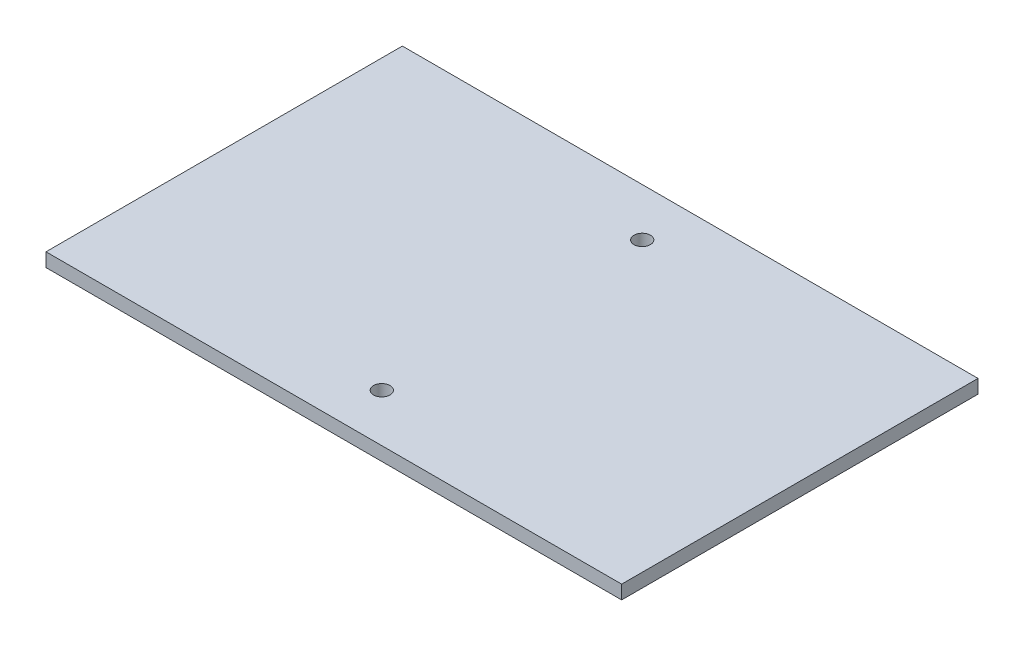
SolidWorks part; units mm, degrees
ref_plane "Front Plane" through (0, 0, 0) normal (0, 0, 1) x (1, 0, 0)
ref_plane "Top Plane" through (0, 0, 0) normal (0, 1, 0) x (1, 0, 0)
ref_plane "Right Plane" through (0, 0, 0) normal (1, 0, 0) x (0, 0, -1)
sketch "Sketch1" plane through (0, 0, 0) normal (0, 1, 0) x (1, 0, 0)
  line L1 (-105, 60) -> (105, 60)
  line L2 (-105, 60) -> (-105, -60)
  line L3 (-105, -60) -> (105, -60)
  line L4 (105, 60) -> (105, -60)
  line L5 (-105, 60) -> (105, -60) construction
  line L6 (-105, -60) -> (105, 60) construction
  point P0 (0, 0)
  dimension "D1" = 210
  dimension "D2" = 120
extrude "Boss-Extrude1" add sketch "Sketch1" along normal blind 5
sketch "Sketch2" plane through (0, 5, 0) normal (0, 1, 0) x (1, 0, 0)
  line L1 (-90, 45) -> (90, 45) construction
  line L2 (-90, 45) -> (-90, -45) construction
  line L3 (-90, -45) -> (90, -45) construction
  line L4 (105, -60) -> (105, 60)
  line L5 (105, 60) -> (-105, 60)
  line L6 (-105, 60) -> (-105, -60)
  line L7 (-105, -60) -> (105, -60)
  line L8 (105, -60) -> (105, 60) construction
  line L9 (105, 60) -> (-105, 60) construction
  line L10 (-105, 60) -> (-105, -60) construction
  line L11 (-105, -60) -> (105, -60) construction
  line L12 (90, 45) -> (90, -45) construction
  line L13 (-90, 45) -> (90, -45) construction
  line L14 (-90, -45) -> (90, 45) construction
  circle A0 centre (-90, 45) radius 6
  circle A1 centre (90, 45) radius 6
  circle A2 centre (90, -45) radius 6
  circle A3 centre (-90, -45) radius 6
  circle A4 centre (-90, 45) radius 9
  circle A5 centre (-90, -45) radius 9
  circle A6 centre (90, 45) radius 9
  circle A7 centre (90, -45) radius 9
  point P2 (0, 0)
  dimension "D4" = 12
  dimension "D5" = 3
  dimension "D2" = 15
  dimension "D3" = 15
  dimension "D1" = 0
sketch "Sketch3" plane through (0, 5, 0) normal (0, 1, 0) x (1, 0, 0)
  line L0 (0, 60) -> (0, -60) construction
  line L1 (105, 60) -> (-105, 60) construction
  line L2 (-105, -60) -> (105, -60) construction
  line L3 (-105, 0) -> (105, 0) construction
  line L4 (-105, 60) -> (-105, -60) construction
  line L5 (105, -60) -> (105, 60) construction
  circle A0 centre (0, 47.5) radius 3
  circle A1 centre (0, -47.5) radius 3
  dimension "D1" = 6
  dimension "D2" = 95
extrude "Cut-Extrude1" cut sketch "Sketch3" against normal blind 10
sketch "Sketch4" plane through (0, 0, 60) normal (0, 0, 1) x (1, 0, 0)
  line L4 (-105, 0) -> (105, 0)
  line L5 (105, 0) -> (105, 5)
  line L6 (105, 5) -> (-105, 5)
  line L7 (-105, 5) -> (-105, 0)
  line L8 (-105, 0) -> (105, 0)
  line L9 (105, 0) -> (105, 5)
  line L10 (105, 5) -> (-105, 5)
  line L11 (-105, 5) -> (-105, 0)
  dimension "D1" = 0
extrude "Boss-Extrude2" add sketch "Sketch4" along normal blind 5
sketch "Sketch5" plane through (0, 0, -60) normal (0, 0, -1) x (-1, 0, 0)
  line L4 (-105, 0) -> (105, 0)
  line L5 (105, 0) -> (105, 5)
  line L6 (105, 5) -> (-105, 5)
  line L7 (-105, 5) -> (-105, 0)
  line L8 (-105, 0) -> (105, 0)
  line L9 (105, 0) -> (105, 5)
  line L10 (105, 5) -> (-105, 5)
  line L11 (-105, 5) -> (-105, 0)
  dimension "D1" = 0
extrude "Boss-Extrude3" add sketch "Sketch5" along normal blind 5
sketch "Sketch6" plane through (0, 0, 0) normal (0, -1, 0) x (1, 0, 0)
  line L0 (-105, 60) -> (105, 60) construction
  line L1 (-105, -65) -> (-105, 65) construction
  line L2 (105, 65) -> (105, -65) construction
  line L3 (-105, -60) -> (105, -60) construction
  line L4 (-105, 65) -> (105, 65) construction
  line L6 (-105, 0) -> (105, 0) construction
  dimension "D1" = 120
  dimension "D2" = 5
